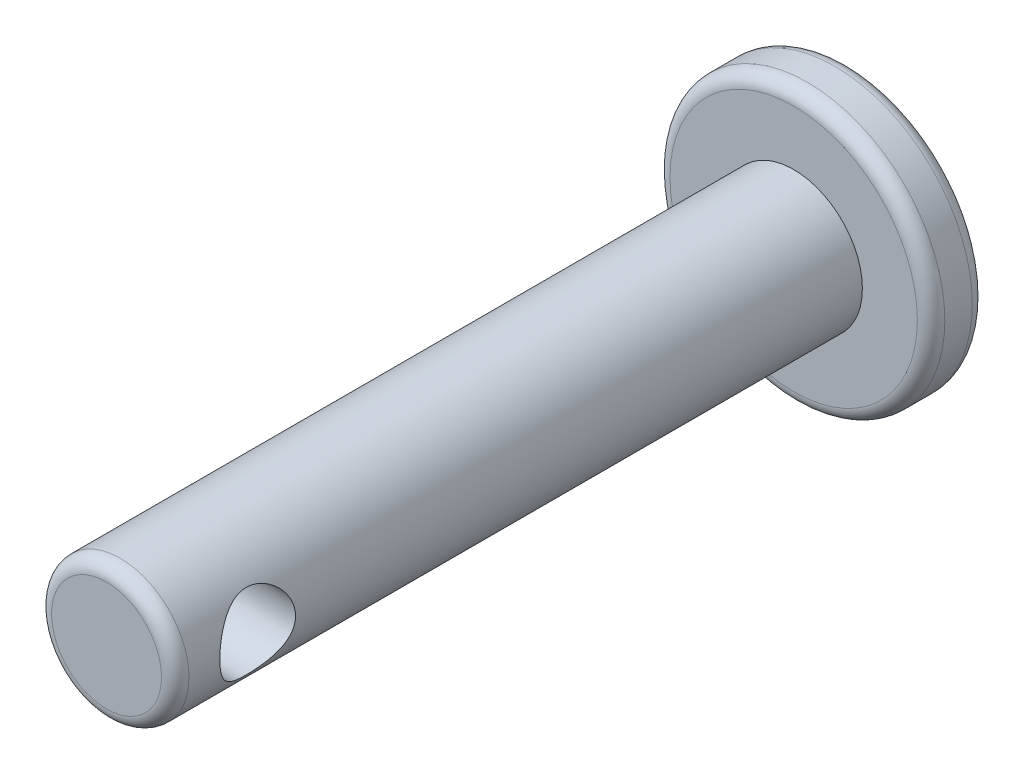
SolidWorks part; units mm, degrees
ref_plane "Front Plane" through (0, 0, 0) normal (0, 0, 1) x (1, 0, 0)
ref_plane "Top Plane" through (0, 0, 0) normal (0, 1, 0) x (1, 0, 0)
ref_plane "Right Plane" through (0, 0, 0) normal (1, 0, 0) x (0, 0, -1)
sketch "Sketch1" plane through (0, 0, 0) normal (0, 0, 1) x (1, 0, 0)
  circle A0 centre (0, 0) radius 3.175
  dimension "D1" = 6.35
extrude "Boss-Extrude1" add sketch "Sketch1" along normal blind 31.75
sketch "Sketch2" plane through (0, 0, 0) normal (0, 0, -1) x (-1, 0, 0)
  circle A0 centre (0, 0) radius 6.35
  dimension "D1" = 12.7
extrude "Boss-Extrude2" add sketch "Sketch2" along normal blind 2.54
sketch "Sketch3" plane through (0, 0, 0) normal (1, 0, 0) x (0, 0, -1)
  line L0 (0, 3.175) -> (0, -3.175) construction
  circle A0 centre (-27.94, 0) radius 1.75
  dimension "D2" = 3.5
  dimension "D1" = 27.94
extrude "Cut-Extrude1" cut sketch "Sketch3" against normal through all both and the other way through all
fillet "Fillet2" radius 0.635 3 edges at (3.175, 0, 31.75) (-6.35, 0, -2.54) (-6.35, 0, 0)
